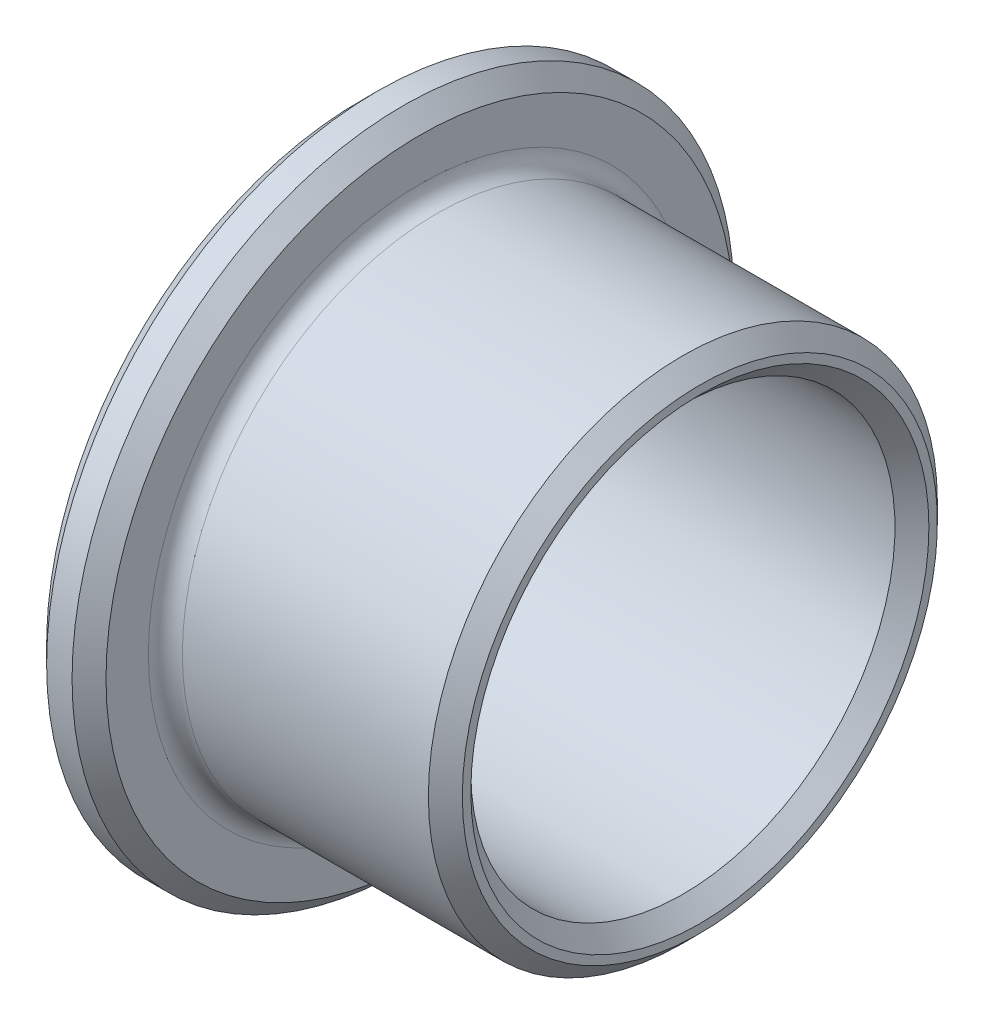
SolidWorks part; units mm, degrees
material "Phosphor bronze 10% D, UNS C52400"
ref_plane "Front Plane" through (0, 0, 0) normal (0, 0, 1) x (1, 0, 0)
ref_plane "Top Plane" through (0, 0, 0) normal (0, 1, 0) x (1, 0, 0)
ref_plane "Right Plane" through (0, 0, 0) normal (1, 0, 0) x (0, 0, -1)
sketch "Sketch1" plane through (0, 0, 0) normal (0, 0, 1) x (1, 0, 0)
  line L0 (0, 12.5) -> (20, 12.5)
  line L1 (20, 12.5) -> (20, 15)
  line L2 (20, 15) -> (3.5, 15)
  line L3 (3.5, 15) -> (3.5, 19.5)
  line L4 (3.5, 19.5) -> (0, 19.5)
  line L5 (0, 19.5) -> (0, 12.5)
  line L6 (0, 0) -> (44.8454, 0) construction
  dimension "D1" = 25
  dimension "D2" = 3.5
  dimension "D3" = 39
  dimension "D4" = 20
  dimension "D5" = 30
revolve "Revolve1" add sketch "Sketch1" angle 360 about L6
chamfer "Chamfer1" distance 1 angle 45 5 edges at (0, 0, 12.5) (20, 0, 12.5) (3.5, 0, 19.5) (0, 0, 19.5) (20, 0, 15)
fillet "Fillet1" radius 1 1 edges at (3.5, 0, 15)
move or copy body "Body-Move/Copy1" [suppressed] bodies to move or copy 101
